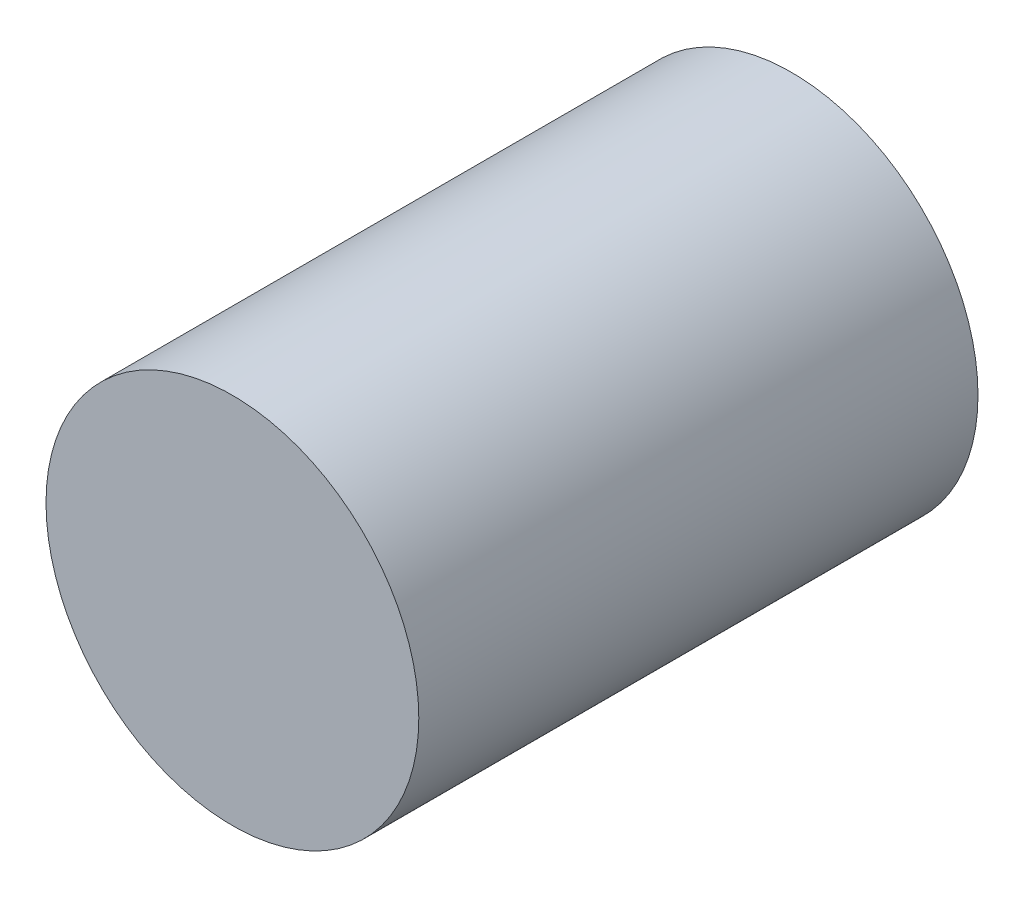
SolidWorks part; units mm, degrees
ref_plane "Plan de face" through (0, 0, 0) normal (0, 0, 1) x (1, 0, 0)
ref_plane "Plan de dessus" through (0, 0, 0) normal (0, 1, 0) x (1, 0, 0)
ref_plane "Plan de droite" through (0, 0, 0) normal (1, 0, 0) x (0, 0, -1)
sketch "Esquisse1" plane through (0, 0, 0) normal (0, 0, 1) x (1, 0, 0)
  circle A0 centre (0, 0) radius 20
  dimension "D1" = 40
extrude "Boss.-Extru.1" add sketch "Esquisse1" along normal mid plane 60
